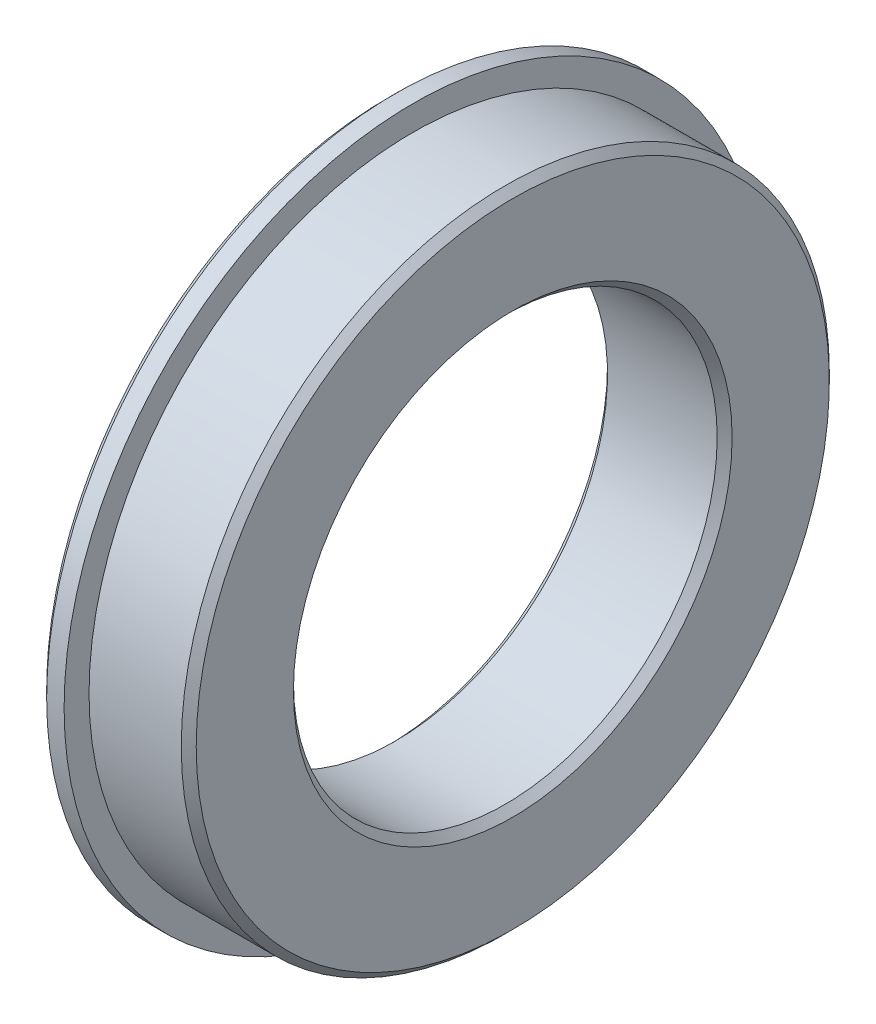
SolidWorks part; units mm, degrees
material "镍"
ref_plane "前视基准面" through (0, 0, 0) normal (0, 0, 1) x (1, 0, 0)
ref_plane "上视基准面" through (0, 0, 0) normal (0, 1, 0) x (1, 0, 0)
ref_plane "右视基准面" through (0, 0, 0) normal (1, 0, 0) x (0, 0, -1)
sketch "草图1" plane through (0, 0, 0) normal (1, 0, 0) x (0, 0, -1)
  circle A0 centre (0, 0) radius 8.5
  circle A1 centre (0, 0) radius 14
  dimension "D1" = 17
  dimension "D2" = 28
extrude "凸台-拉伸1" add sketch "草图1" along normal blind 5
sketch "草图2" plane through (5, 0, 0) normal (1, 0, 0) x (0, 0, -1)
  circle A0 centre (0, 0) radius 13
  circle A1 centre (0, 0) radius 16.1272
  dimension "D1" = 26
extrude "切除-拉伸1" cut sketch "草图2" against normal blind 4
chamfer "倒角1" distance 0.3 angle 45 4 edges at (5, 0, -13) (0, 0, -14) (5, 0, -8.5) (0, 0, -8.5)
